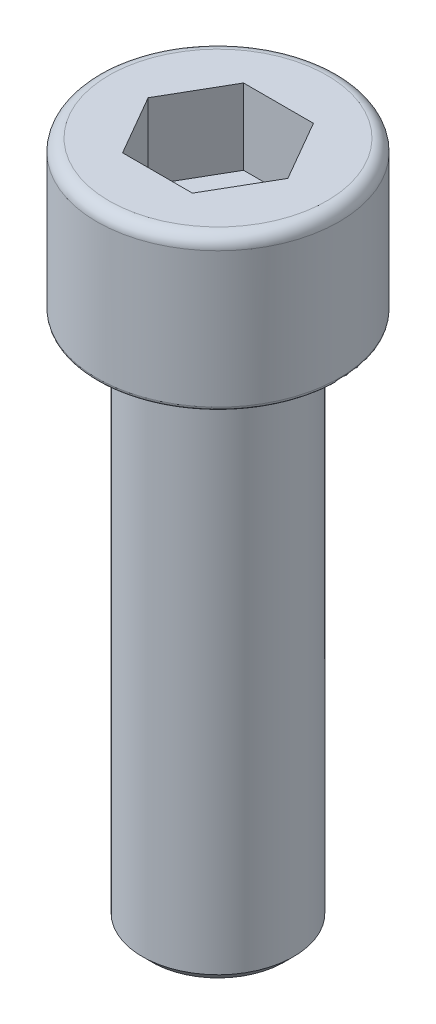
SolidWorks part; units mm, degrees
material "Plain Carbon Steel"
ref_plane "Front Plane" through (0, 0, 0) normal (0, 0, 1) x (1, 0, 0)
ref_plane "Top Plane" through (0, 0, 0) normal (0, 1, 0) x (1, 0, 0)
ref_plane "Right Plane" through (0, 0, 0) normal (1, 0, 0) x (0, 0, -1)
sketch "Sketch1" plane through (0, 0, 0) normal (0, 0, 1) x (1, 0, 0)
  line L0 (0, 0) -> (8, 0)
  line L1 (8, 0) -> (8, -10)
  line L2 (8, -10) -> (5, -10)
  line L3 (5, -10) -> (5, -45)
  line L4 (5, -45) -> (0, -45)
  line L5 (0, -45) -> (0, 0)
  line L6 (0, -50) -> (0, 5) construction
  dimension "D1" = 5
  dimension "D2" = 5
  dimension "H" = 10
  dimension "L" = 35
  dimension "D" = 10
  dimension "A" = 16
revolve "Revolve1" add sketch "Sketch1" angle 360 about L6
sketch "Sketch2" plane through (0, 0, 0) normal (0, 1, 0) x (1, 0, 0)
  line L7 (4.6188, 0) -> (2.3094, 4)
  line L8 (2.3094, 4) -> (-2.3094, 4)
  line L9 (-2.3094, 4) -> (-4.6188, 0)
  line L10 (-4.6188, 0) -> (-2.3094, -4)
  line L11 (-2.3094, -4) -> (2.3094, -4)
  line L12 (2.3094, -4) -> (4.6188, 0)
  circle A0 centre (0, 0) radius 4 construction
  dimension "D1" = 8
extrude "Cut-Extrude1" cut sketch "Sketch2" against normal blind 5
fillet "Fillet3" radius 0.8 1 edges at (0, 0, -8)
chamfer "Chamfer1" distance 0.625 angle 45 1 edges at (0, -45, -5)
cosmetic thread "Cosmetic Thread1" parameters "B"=30.5, "D2"=8.344
ref_plane "ThreadStop" through (0, -13.75, 0) normal (0, -1, 0) x (-1, 0, 0)
fillet "Fillet4" radius 0.25 2 edges at (0, -10, -5) (0, -10, -8)
